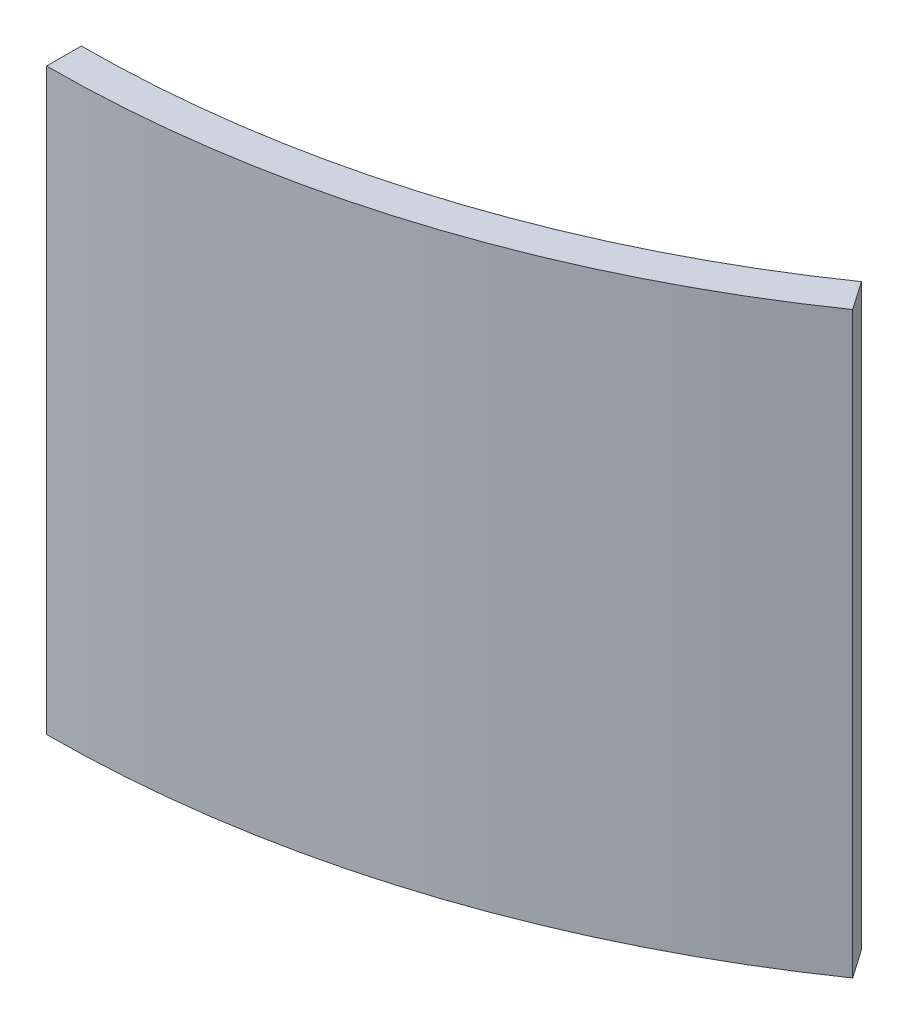
SolidWorks part; units mm, degrees
ref_plane "Front Plane" through (0, 0, 0) normal (0, 0, 1) x (1, 0, 0)
ref_plane "Top Plane" through (0, 0, 0) normal (0, 1, 0) x (1, 0, 0)
ref_plane "Right Plane" through (0, 0, 0) normal (1, 0, 0) x (0, 0, -1)
sketch "Sketch1" plane through (0, 0, 0) normal (0, 1, 0) x (1, 0, 0)
  line L0 (0, -90) -> (0, -93)
  line L1 (51.3157, -73.9371) -> (53.0262, -76.4017)
  arc A0 (0, -90) -> (51.3157, -73.9371) centre (0, 0) ccw
  arc A1 (0, -93) -> (53.0262, -76.4017) centre (0, 0) ccw
  point P7 (0, 0)
  dimension "D1" = 90
  dimension "D2" = 93
extrude "Boss-Extrude1" add sketch "Sketch1" along normal blind 50
